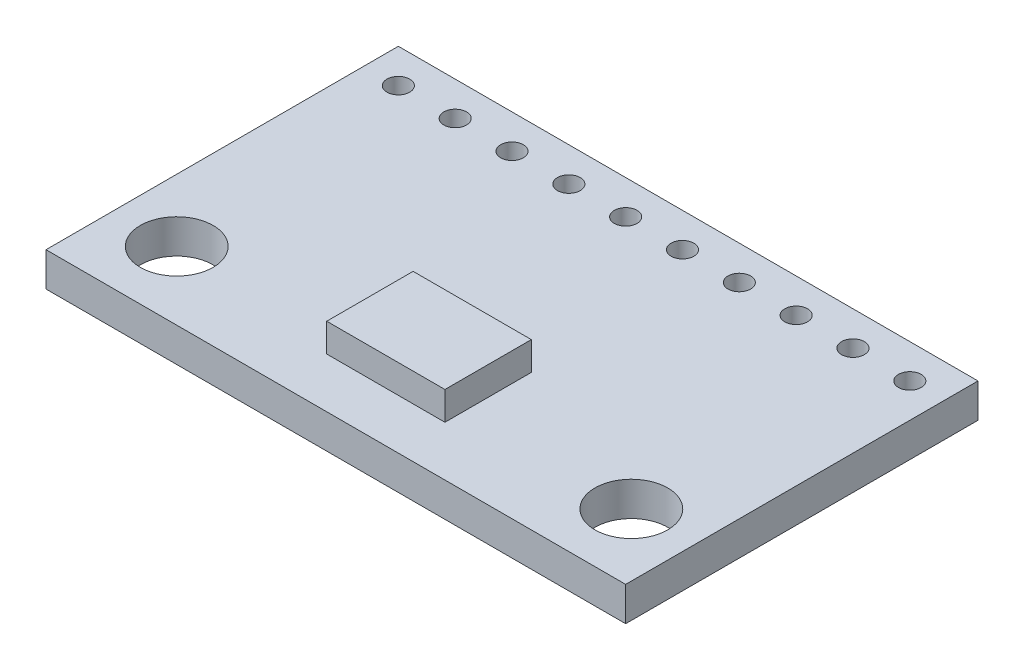
SolidWorks part; units mm, degrees
ref_plane "Front Plane" through (0, 0, 0) normal (0, 0, 1) x (1, 0, 0)
ref_plane "Top Plane" through (0, 0, 0) normal (0, 1, 0) x (1, 0, 0)
ref_plane "Right Plane" through (0, 0, 0) normal (1, 0, 0) x (0, 0, -1)
sketch "Sketch1" plane through (0, 0, 0) normal (0, 1, 0) x (1, 0, 0)
  line L0 (0, 0) -> (0, 15.363) construction
  line L1 (-12.75, 7.75) -> (12.75, 7.75)
  line L2 (-12.75, 7.75) -> (-12.75, -7.75)
  line L3 (-12.75, -7.75) -> (12.75, -7.75)
  line L4 (12.75, 7.75) -> (12.75, -7.75)
  line L5 (-12.75, 7.75) -> (12.75, -7.75) construction
  line L6 (-12.75, -7.75) -> (12.75, 7.75) construction
  circle A0 centre (-10, -4.75) radius 1.6
  circle A1 centre (10, -4.75) radius 1.6
  point P0 (0, 0)
  point P12 (10, -4.3649)
  dimension "D3" = 20
  dimension "D5" = 3.2
  dimension "D1" = 15.5
  dimension "D2" = 25.5
  dimension "D4" = 3
extrude "Boss-Extrude1" add sketch "Sketch1" along normal blind 1.5
sketch "Sketch2" plane through (0, 1.5, 0) normal (0, 1, 0) x (1, 0, 0)
  line L0 (-12.75, -7.75) -> (12.75, -7.75) construction
  line L1 (-2.6, -1.75) -> (2.6, -1.75)
  line L2 (-2.6, -1.75) -> (-2.6, -5.55)
  line L3 (-2.6, -5.55) -> (2.6, -5.55)
  line L4 (2.6, -1.75) -> (2.6, -5.55)
  line L5 (-2.6, -1.75) -> (2.6, -5.55) construction
  line L6 (-2.6, -5.55) -> (2.6, -1.75) construction
  point P0 (0, -3.65)
  point P7 (0, 0)
  dimension "D1" = 2.2
  dimension "D2" = 5.2
  dimension "D3" = 3.8
extrude "Boss-Extrude2" add sketch "Sketch2" along normal blind 1.25
sketch "Sketch3" plane through (0, 1.5, 0) normal (0, 1, 0) x (1, 0, 0)
  line L0 (12.75, 7.75) -> (-12.75, 7.75) construction
  line L1 (-12.75, 7.75) -> (-12.75, -7.75) construction
  circle A0 centre (-11.25, 6.25) radius 0.5
  point P2 (0, 0)
  dimension "D1" = 1
  dimension "D2" = 1.5
  dimension "D3" = 1.5
extrude "Cut-Extrude1" cut sketch "Sketch3" against normal through all
pattern_linear "LPattern1" count 10 spacing 2.5 along (1, 0, 0) of "Cut-Extrude1"
